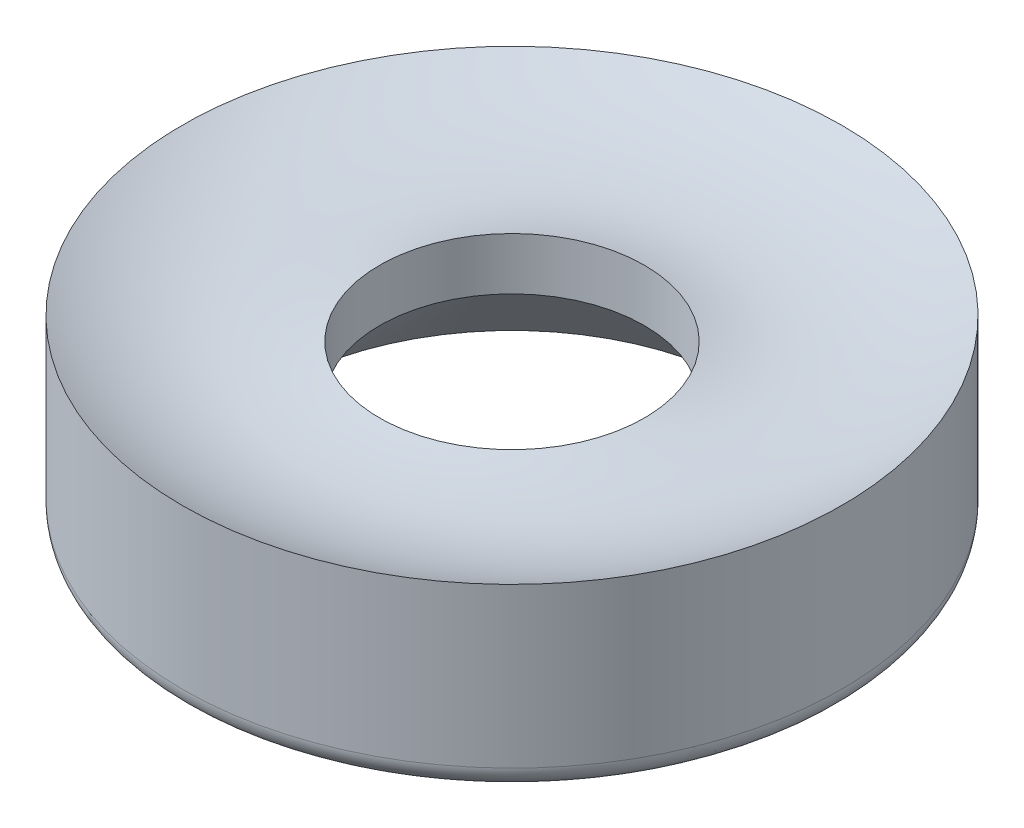
SolidWorks part; units mm, degrees
material "Nylon 101"
ref_plane "Front Plane" through (0, 0, 0) normal (0, 0, 1) x (1, 0, 0)
ref_plane "Top Plane" through (0, 0, 0) normal (0, 1, 0) x (1, 0, 0)
ref_plane "Right Plane" through (0, 0, 0) normal (1, 0, 0) x (0, 0, -1)
sketch "Sketch1" plane through (0, 0, 0) normal (0, 1, 0) x (1, 0, 0)
  circle A0 centre (0, 0) radius 36.83
extrude "Boss-Extrude1" add sketch "Sketch1" along normal blind 20.32
fillet "Fillet1" radius 2.54 1 edges at (0, 0, 36.83)
sketch "Sketch2" plane through (0, 0, 0) normal (0, 1, 0) x (1, 0, 0)
  circle A0 centre (0, 0) radius 26.67
  dimension "D1" = 53.34
ref_plane "Plane1" through (0, 11.938, 0) normal (0, 1, 0) x (1, 0, 0)
sketch "Sketch3" plane through (0, 11.938, 0) normal (0, 1, 0) x (1, 0, 0)
  circle A0 centre (0, 0) radius 14.7955
  dimension "D1" = 29.591
loft "Cut-Loft1" cut profiles "Sketch2", "Sketch3"
sketch "Sketch4" plane through (0, 11.938, 0) normal (0, -1, 0) x (1, 0, 0)
  circle A0 centre (0, 0) radius 14.7955 construction
  circle A1 centre (0, 0) radius 14.7955
extrude "Cut-Extrude1" cut sketch "Sketch4" against normal blind 76.2
ref_plane "Plane2" through (0, 13.97, 0) normal (0, 1, 0) x (1, 0, 0)
ref_plane "Plane3" through (0, 0, 36.83) normal (0, 0, 1) x (1, 0, 0)
sketch "Sketch17" plane through (0, 0, 0) normal (1, 0, 0) x (0, 0, -1)
  line L0 (0, 0) -> (0, 17.78) construction
  line L1 (36.83, 20.32) -> (-36.83, 20.32) construction
  line L3 (36.83, 20.32) -> (14.7955, 20.32)
  line L4 (14.7955, 20.32) -> (14.7955, 17.78)
  arc A0 (36.83, 20.32) -> (14.7955, 17.78) centre (22.4059, 48.6044) cw
  dimension "D2" = 31.75
  dimension "D1" = 17.78
  dimension "D3" = 14.7955
revolve "Cut-Revolve1" cut sketch "Sketch17" angle 360 about L0
sketch "Sketch18" plane through (0, 0, 0) normal (0, -1, 0) x (1, 0, 0)
  line L0 (0, 0) -> (0, 30.4312) construction
  line L1 (30.4312, 0) -> (0, 0) construction
  line L2 (0, 0) -> (0, -30.4312) construction
  line L3 (0, 0) -> (-30.4312, 0) construction
  arc A0 (0, 30.4312) -> (30.4312, 0) centre (0, 0) cw construction
  circle A1 centre (0, 30.4312) radius 3.175
  circle A2 centre (-30.4312, 0) radius 3.175
  circle A3 centre (0, -30.4312) radius 3.175
  circle A4 centre (30.4312, 0) radius 3.175
  dimension "D1" = 30.4312
  dimension "D2" = 6.35
  dimension "D3" = 30.4312
  dimension "D4" = 30.4312
  dimension "D5" = 30.4312
extrude "Cut-Extrude2" cut sketch "Sketch18" against normal blind 6.35
sketch "Sketch19" plane through (0, 0, 0) normal (0, -1, 0) x (1, 0, 0)
  line L0 (0, -30.4312) -> (3.175, -30.4312) construction
  line L1 (3.175, -30.4312) -> (4.445, -30.4312) construction
  line L3 (4.2597, -31.7012) -> (2.9099, -31.7012)
  line L4 (4.2597, -29.1612) -> (2.9099, -29.1612)
  circle A0 centre (0, -30.4312) radius 3.175 construction
  arc A1 (4.2597, -31.7012) -> (4.2597, -29.1612) centre (0, -30.4312) ccw
  arc A2 (2.9099, -31.7012) -> (2.9099, -29.1612) centre (0, -30.4312) ccw
  dimension "D1" = 1.27
  dimension "D2" = 2.54
extrude "Cut-Extrude3" cut sketch "Sketch19" against normal up to surface (6.35 mm away) up to face at (0, 6.35, -33.6062)
sketch "Sketch20" plane through (0, 6.35, 0) normal (0, -1, 0) x (1, 0, 0)
  line L0 (-1.27, -34.6909) -> (-1.27, -33.3411)
  line L1 (2.9099, -31.7012) -> (4.2597, -31.7012) construction
  line L2 (2.9099, -31.7012) -> (4.2597, -31.7012)
  arc A0 (-1.27, -34.6909) -> (4.2597, -31.7012) centre (0, -30.4312) ccw
  arc A1 (2.9099, -29.1612) -> (2.9099, -31.7012) centre (0, -30.4312) ccw construction
  arc A2 (-1.27, -33.3411) -> (2.9099, -31.7012) centre (0, -30.4312) ccw
  point P15 (0, -30.4312)
  dimension "D1" = 4.445
extrude "Cut-Extrude4" cut sketch "Sketch20" along normal blind 2.54
pattern_circular "CirPattern1" count 4 over 360 about axis through (0, 0, 0) along (0, 1, 0) of "Cut-Extrude3", "Cut-Extrude4"
sketch "Sketch21" plane through (0, 0, 0) normal (0, -1, 0) x (1, 0, 0)
  line L0 (34.29, 0) -> (0, 0) construction
  line L1 (0, 0) -> (0, -34.29) construction
  line L2 (30.3335, 30.3335) -> (0, 0) construction
  arc A0 (0, 34.29) -> (-34.29, 0) centre (0, 0) ccw
  arc A1 (34.29, 0) -> (0, -34.29) centre (0, 0) cw
  point P1 (24.2467, -24.2467)
  point P9 (-24.2467, 24.2467)
  dimension "D1" = 45
